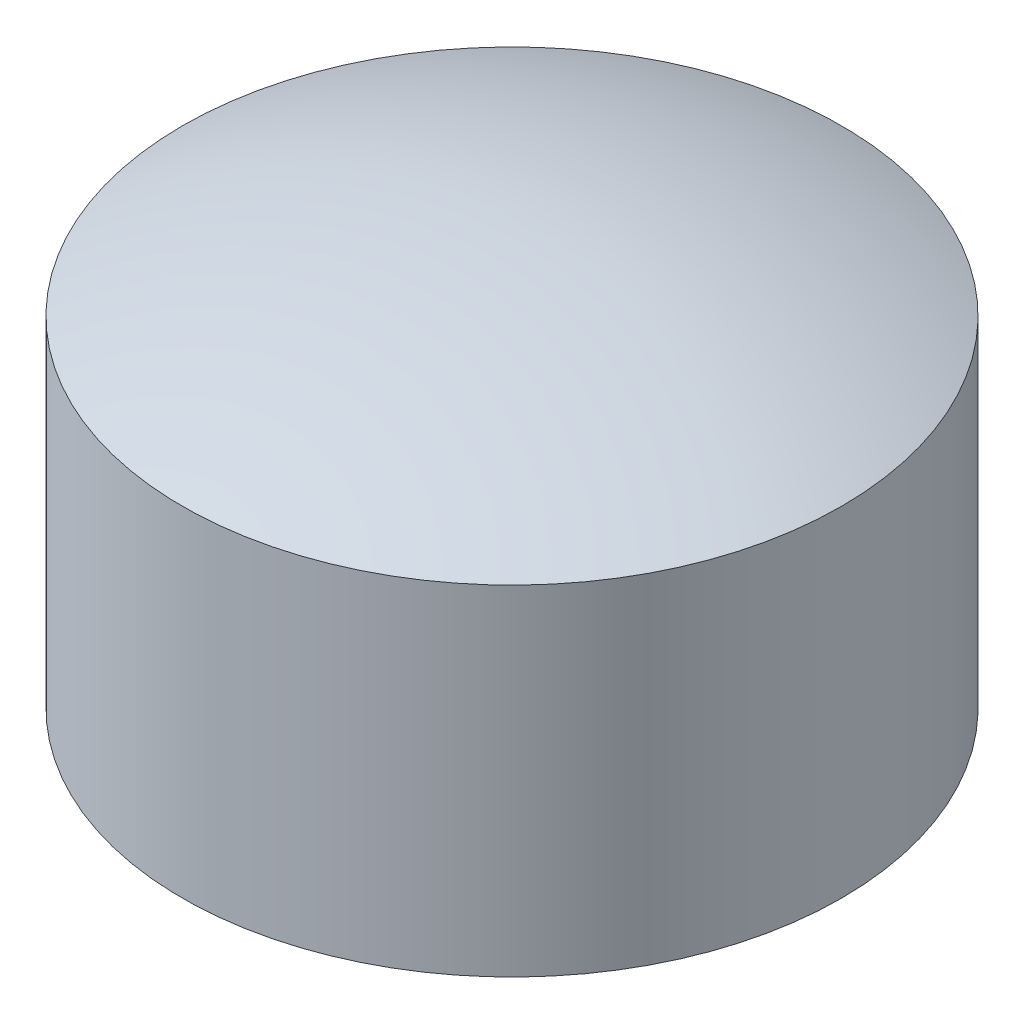
SolidWorks part; units mm, degrees
material "PVC Rigid"
ref_plane "Front Plane" through (0, 0, 0) normal (0, 0, 1) x (1, 0, 0)
ref_plane "Top Plane" through (0, 0, 0) normal (0, 1, 0) x (1, 0, 0)
ref_plane "Right Plane" through (0, 0, 0) normal (1, 0, 0) x (0, 0, -1)
sketch "Sketch2" plane through (0, 0, 0) normal (0, 0, 1) x (1, 0, 0)
  line L0 (0, 67.6046) -> (0, -54.8953) construction
  line L1 (83.5, -54.8953) -> (83.5, 31.1047)
  line L2 (0, 49.0797) -> (0, 49.1047)
  line L3 (80, -54.8953) -> (80, 29.1093)
  line L5 (83.5, -54.8953) -> (80, -54.8953)
  line L6 (0, 49.0797) -> (0, 45.5797)
  line L8 (-83.5, -54.8953) -> (-83.5, 5.311) construction
  line L9 (-80, -54.8953) -> (-80, 3.979) construction
  arc A0 (0, 49.1047) -> (83.5, 31.1047) centre (0, -153.5689) cw
  arc A3 (83.5, 31.1047) -> (-83.5, 5.311) centre (15.4568, -81.8665) ccw construction
  arc A4 (80, 29.1093) -> (-80, 3.979) centre (15.4568, -81.8665) ccw construction
  spline S0 degree 2 poles (0, 45.5797) (40, 45.5797) (80, 29.1093) knots 0.5 0.5 0.5 1 1 1
  point P7 (0, 49.1047)
  dimension "D1" = 83.5
  dimension "D2" = 86
  dimension "D3" = 104
  dimension "D5" = 3.5
  dimension "D4" = 3.5
revolve "Revolve2" add sketch "Sketch2" angle 360 about L0
